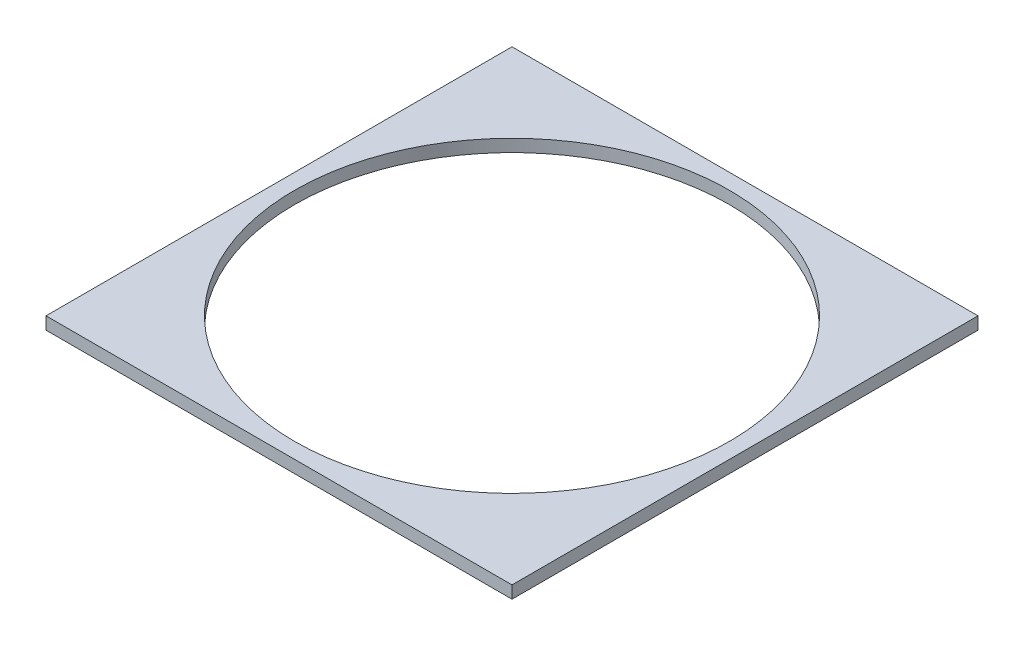
SolidWorks part; units mm, degrees
ref_plane "Front Plane" through (0, 0, 0) normal (0, 0, 1) x (1, 0, 0)
ref_plane "Top Plane" through (0, 0, 0) normal (0, 1, 0) x (1, 0, 0)
ref_plane "Right Plane" through (0, 0, 0) normal (1, 0, 0) x (0, 0, -1)
sketch "Sketch1" plane through (0, 0, 0) normal (0, 1, 0) x (1, 0, 0)
  line L1 (-150, -150) -> (150, -150)
  line L2 (-150, -150) -> (-150, 150)
  line L3 (-150, 150) -> (150, 150)
  line L4 (150, -150) -> (150, 150)
  line L5 (-150, -150) -> (150, 150) construction
  line L6 (-150, 150) -> (150, -150) construction
  point P0 (0, 0)
  dimension "D1" = 300
  dimension "D2" = 300
extrude "Boss-Extrude1" add sketch "Sketch1" along normal blind 8
sketch "Sketch2" plane through (0, 8, 0) normal (0, 1, 0) x (1, 0, 0)
  circle A0 centre (0, 0) radius 140
  dimension "D1" = 280
extrude "Cut-Extrude1" cut sketch "Sketch2" against normal blind 10
